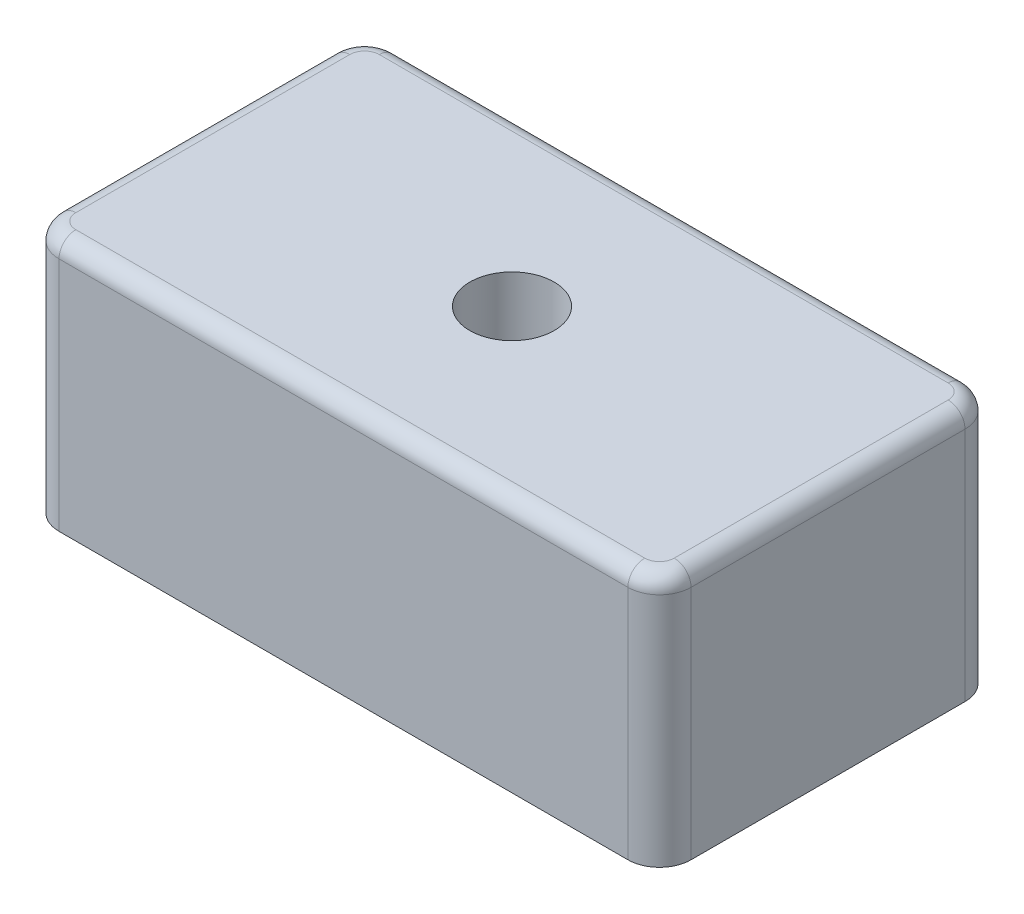
SolidWorks part; units mm, degrees
material "ABS"
ref_plane "Front Plane" through (0, 0, 0) normal (0, 0, 1) x (1, 0, 0)
ref_plane "Top Plane" through (0, 0, 0) normal (0, 1, 0) x (1, 0, 0)
ref_plane "Right Plane" through (0, 0, 0) normal (1, 0, 0) x (0, 0, -1)
sketch "Sketch2" plane through (0, 0, 0) normal (0, 1, 0) x (1, 0, 0)
  line L1 (-15, 8) -> (15, 8)
  line L2 (-15, 8) -> (-15, -8)
  line L3 (-15, -8) -> (15, -8)
  line L4 (15, 8) -> (15, -8)
  line L5 (-15, 8) -> (15, -8) construction
  line L6 (-15, -8) -> (15, 8) construction
  point P0 (0, 0)
  dimension "D1" = 30
  dimension "D2" = 16
extrude "Boss-Extrude1" add sketch "Sketch2" along normal blind 12
sketch "Sketch3" plane through (0, 12, 0) normal (0, 1, 0) x (1, 0, 0)
  circle A0 centre (0, 0) radius 2
  dimension "D1" = 4
extrude "Cut-Extrude1" cut sketch "Sketch3" against normal through all
fillet "Fillet1" radius 1.5 4 edges at (-15, 6, 8) (-15, 6, -8) (15, 6, -8) (15, 6, 8)
fillet "Fillet2" radius 0.8 8 edges at (14.5607, 12, -7.5607) (14.5607, 12, 7.5607) (-14.5607, 12, 7.5607) (-14.5607, 12, -7.5607) (-15, 12, 0) (0, 12, 8) (15, 12, 0) (0, 12, -8)
